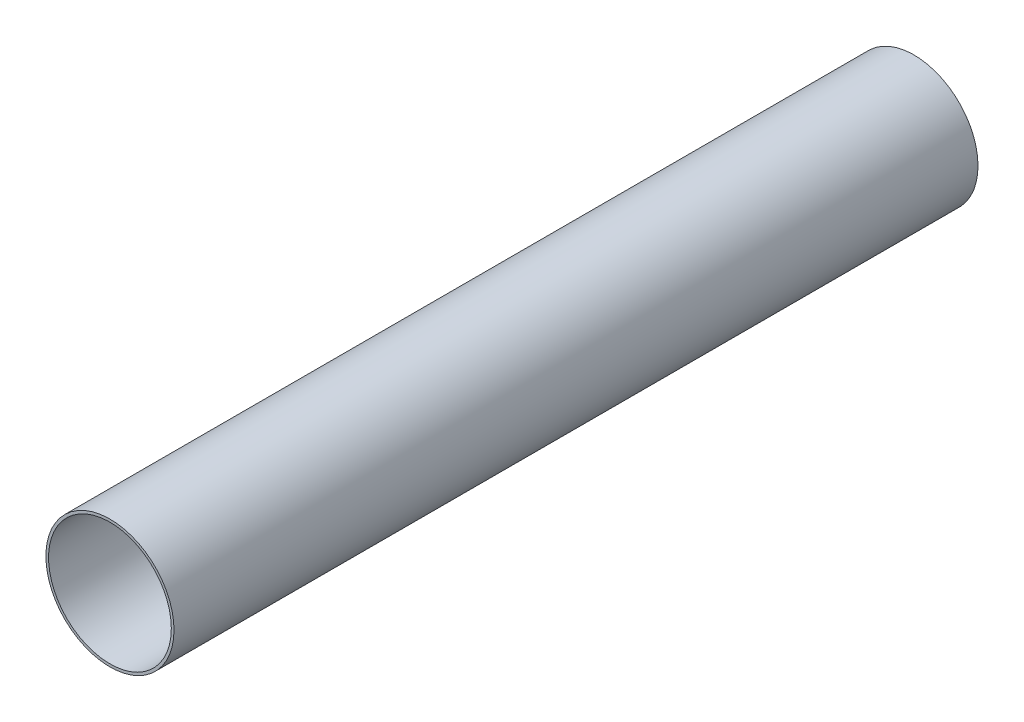
SolidWorks part; units mm, degrees
ref_plane "Front Plane" through (0, 0, 0) normal (0, 0, 1) x (1, 0, 0)
ref_plane "Top Plane" through (0, 0, 0) normal (0, 1, 0) x (1, 0, 0)
ref_plane "Right Plane" through (0, 0, 0) normal (1, 0, 0) x (0, 0, -1)
ref_plane "Plane1"
sketch "Sketch1" plane through (0, 0, 0) normal (0, 0, 1) x (1, 0, 0)
  circle A0 centre (0.1401, 0) radius 55
  circle A1 centre (0.1401, 0) radius 52.7
  dimension "D1" = 110
extrude "Extrusion1" add sketch "Sketch1" along normal blind 690.3 contours A0 A1
